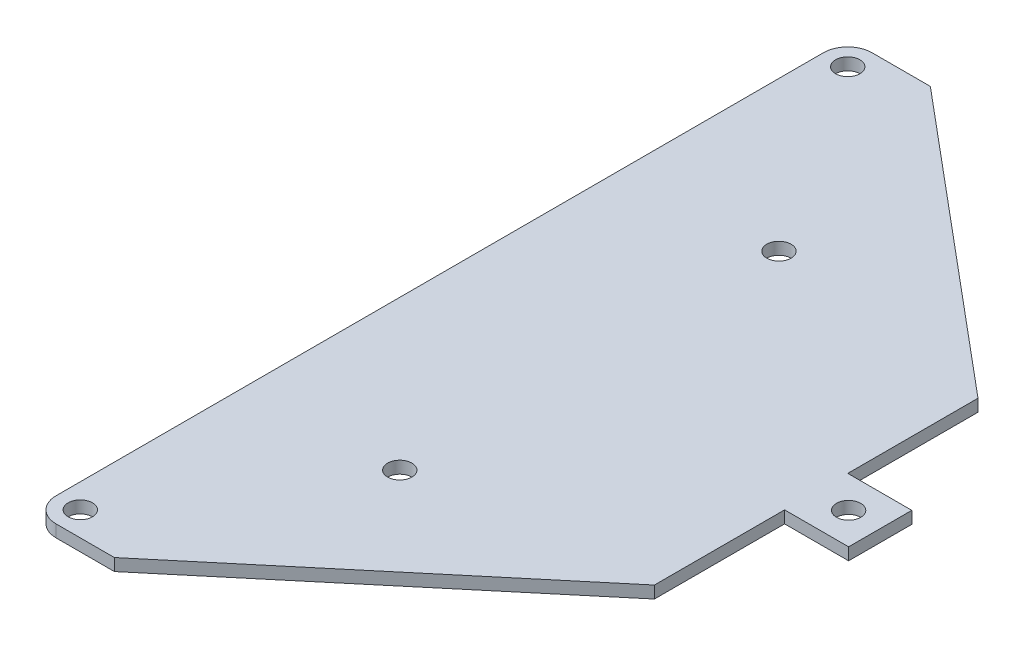
SolidWorks part; units mm, degrees
ref_plane "Front Plane" through (0, 0, 0) normal (0, 0, 1) x (1, 0, 0)
ref_plane "Top Plane" through (0, 0, 0) normal (0, 1, 0) x (1, 0, 0)
ref_plane "Right Plane" through (0, 0, 0) normal (1, 0, 0) x (0, 0, -1)
sketch "Croquis1" plane through (0, 0, 0) normal (0, 1, 0) x (1, 0, 0)
  line L0 (43.47, -43.46) -> (51.37, -43.46)
  line L1 (51.37, -43.46) -> (51.37, -51.26)
  line L2 (51.37, -51.26) -> (43.47, -51.26)
  line L4 (-3, -94.72) -> (-3, 0)
  line L6 (43.47, -43.46) -> (43.47, -27.39)
  line L7 (43.47, -27.39) -> (7.2, 3)
  line L8 (7.2, 3) -> (0, 3)
  line L9 (0, -97.72) -> (7.2, -97.72)
  line L10 (7.2, -97.72) -> (43.47, -67.33)
  line L11 (43.47, -67.33) -> (43.47, -51.26)
  circle A0 centre (0, 0) radius 1.5
  circle A1 centre (0, -94.72) radius 1.5
  circle A2 centre (47.47, -47.36) radius 1.5
  arc A4 (0, -97.72) -> (-3, -94.72) centre (0, -94.72) cw
  arc A5 (-3, 0) -> (0, 3) centre (0, 0) cw
  circle A6 centre (15.47, -23.96) radius 1.5
  circle A7 centre (15.47, -70.76) radius 1.5
  point P21 (0, 0)
  point P22 (-3, -47.36)
  dimension "D2" = 3
  dimension "D5" = 3
  dimension "D1" = 94.72
  dimension "D3" = 47.47
  dimension "D4" = 47.36
  dimension "D6" = 3.9
  dimension "D7" = 3.9
  dimension "D8" = 3.9
  dimension "D9" = 4
  dimension "D11" = 7.2
  dimension "D10" = 39.94
  dimension "D12" = 19.97
  dimension "D13" = 32
  dimension "D14" = 46.8
  dimension "D15" = 23.4
extrude "Saliente-Extruir1" add sketch "Croquis1" along normal blind 1.5
equation "\"D4@Croquis1\"=\"D1@Croquis1\"/2"
equation "\"D12@Croquis1\"=\"D10@Croquis1\"/2"
equation "\"D15@Croquis1\"=\"D14@Croquis1\"/2"
